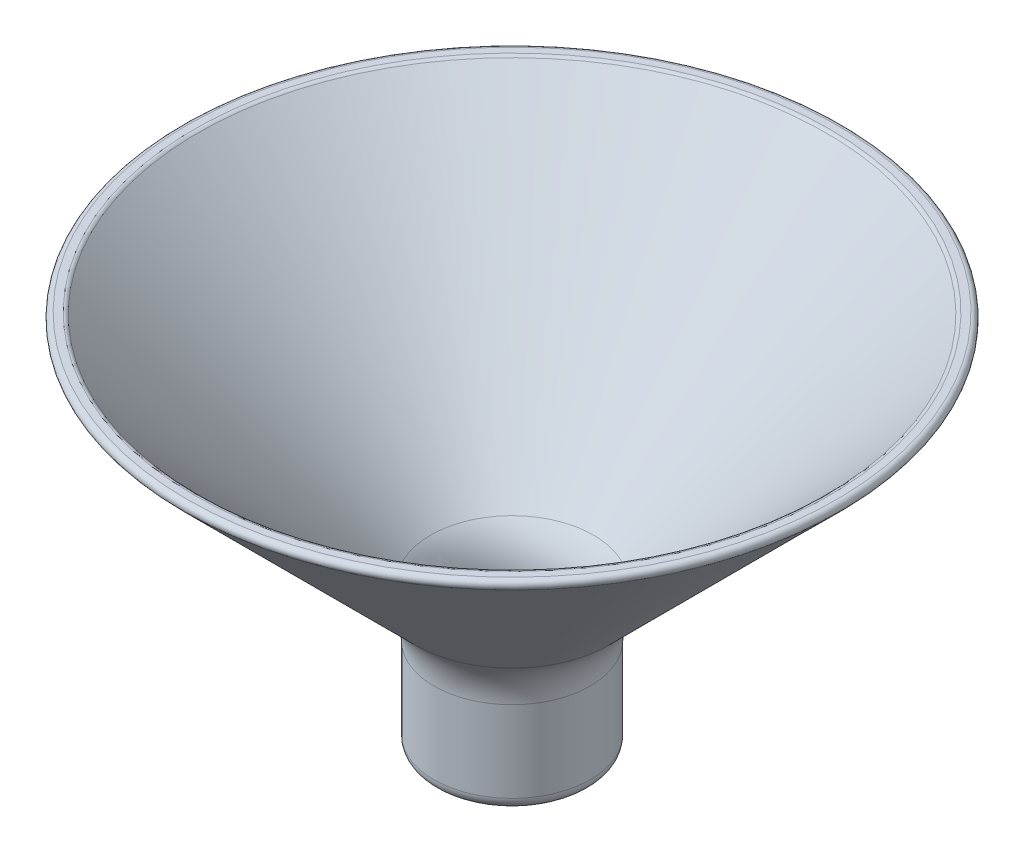
SolidWorks part; units mm, degrees
ref_plane "Front Plane" through (0, 0, 0) normal (0, 0, 1) x (1, 0, 0)
ref_plane "Top Plane" through (0, 0, 0) normal (0, 1, 0) x (1, 0, 0)
ref_plane "Right Plane" through (0, 0, 0) normal (1, 0, 0) x (0, 0, -1)
sketch "Sketch1" plane through (0, 0, 0) normal (0, 0, 1) x (1, 0, 0)
  line L0 (0, 0) -> (2, 0) construction
  line L1 (5, 5.1962) -> (5, 10)
  line L2 (5, 10) -> (25, 30)
  line L3 (0, 0) -> (0, 30) construction
  line L7 (25, 30) -> (26.6971, 30)
  line L9 (2, 0) -> (5, 5.1962)
  line L10 (6.2, 4.8746) -> (6.2, 9.5029)
  line L11 (6.2, 9.5029) -> (26.6971, 30)
  line L12 (6.2, 9.5029) -> (25.4971, 28.8) construction
  line L13 (2, 0) -> (6.2, 0)
  line L14 (3.0392, -0.6) -> (6.2, 4.8746) construction
  line L15 (25.4971, 28.8) -> (26.6971, 28.8) construction
  line L16 (6.2, 4.8746) -> (6.2, 0)
  point P13 (6.1125, 0)
  point P15 (6.2, 4.8746)
  point P16 (6.2, 4.8746)
  dimension "D1" = 5
  dimension "D2" = 10
  dimension "D3" = 135
  dimension "D4" = 30
  dimension "D6" = 2
  dimension "D7" = 60
  dimension "D5" = 1.2
revolve "Revolve1" add sketch "Sketch1" angle 360 about L3
fillet "Fillet1" radius 5 2 edges at (0, 9.5029, -6.2) (0, 10, -5)
fillet "Fillet2" radius 0.4 2 edges at (0, 30, -25) (0, 30, -26.6971)
fillet "Fillet3" radius 1 1 edges at (0, 0, -6.2)
